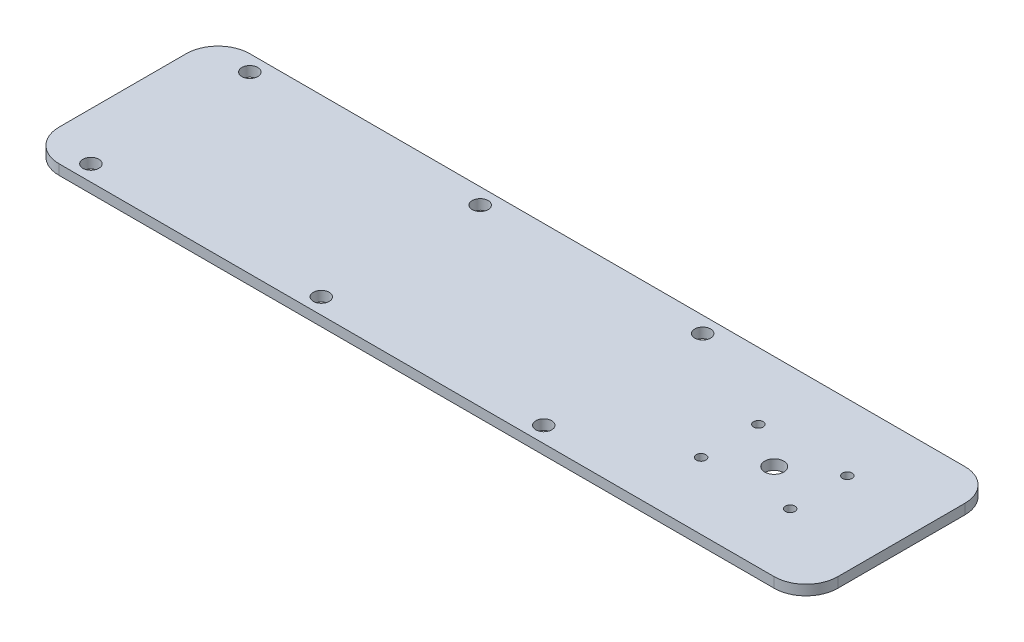
SolidWorks part; units mm, degrees
ref_plane "Front Plane" through (0, 0, 0) normal (0, 0, 1) x (1, 0, 0)
ref_plane "Top Plane" through (0, 0, 0) normal (0, 1, 0) x (1, 0, 0)
ref_plane "Right Plane" through (0, 0, 0) normal (1, 0, 0) x (0, 0, -1)
sketch "Sketch1" plane through (0, 0, 0) normal (0, 1, 0) x (1, 0, 0)
  line L0 (-55, 0) -> (0, 0) construction
  line L1 (-55, 30) -> (190, 30)
  line L2 (-55, 30) -> (-55, -30)
  line L3 (-55, -30) -> (190, -30)
  line L4 (190, 30) -> (190, -30)
  point P7 (150, 0)
  dimension "D1" = 60
  dimension "D2" = 55
  dimension "D3" = 150
  dimension "D4" = 40
extrude "Boss-Extrude1" add sketch "Sketch1" along normal blind 3.175
fillet "Fillet1" radius 10 4 edges at (-55, 1.5875, 30) (-55, 1.5875, -30) (190, 1.5875, 30) (190, 1.5875, -30)
hole_wizard "Ø6.0mm Dowel Hole1" positions "Sketch2" profile "Sketch3" hole size "Ø6.0" standard "DIN" end condition up to next
sketch "Sketch2" plane through (0, 3.175, 0) normal (0, 1, 0) x (1, 0, 0)
  point P0 (150, 0)
  dimension "D1" = 150
sketch "Sketch3" plane through (150, 3.175, 0) normal (1, 0, 0) x (0, 0, 1)
  line L0 (0, 0) -> (0, 3.175)
  line L1 (0, 3.175) -> (3, 3.175)
  line L2 (3, 3.175) -> (3, 0)
  line L5 (3, 0) -> (0, 0)
  line L11 (0, -6.35) -> (0, 107.95) construction
  dimension "Thru Hole Dia." = 6
  dimension "Thru Hole Depth" = 3.175
hole_wizard "Ø3.0mm Dowel Hole1" positions "Sketch4" profile "Sketch5" hole size "Ø3.0" standard "ANSI Metric" end condition up to next
sketch "Sketch4" plane through (0, 3.175, 0) normal (0, 1, 0) x (1, 0, 0)
  line L0 (164, -9) -> (136, -9) construction
  line L1 (164, -9) -> (164, 9) construction
  circle A0 centre (150, 0) radius 3 construction
  point P0 (164, -9)
  point P7 (136, -9)
  point P8 (136, 9)
  point P9 (164, 9)
  dimension "D3" = 28
  dimension "D4" = 18
  dimension "D5" = 14
  dimension "D6" = 9
  dimension "D1" = 2
  dimension "D2" = 2
sketch "Sketch5" plane through (164, 3.175, 9) normal (1, 0, 0) x (0, 0, 1)
  line L0 (0, 0) -> (0, 3.175)
  line L1 (0, 3.175) -> (1.5, 3.175)
  line L2 (1.5, 3.175) -> (1.5, 0)
  line L5 (1.5, 0) -> (0, 0)
  line L11 (0, -6.35) -> (0, 107.95) construction
  dimension "Thru Hole Dia." = 3
  dimension "Thru Hole Depth" = 3.175
hole_wizard "Ø5.0mm Dowel Hole1" positions "Sketch6" profile "Sketch7" hole size "Ø5.0" standard "DIN" end condition through all
sketch "Sketch6" plane through (0, 3.175, 0) normal (0, 1, 0) x (1, 0, 0)
  line L0 (-45, -30) -> (180, -30) construction
  line L1 (32.5, -25) -> (102.5, -25) construction
  line L2 (-55, 0) -> (190, 0) construction
  line L3 (-55, 20) -> (-55, -20) construction
  line L4 (190, -20) -> (190, 20) construction
  line L5 (67.5, 30) -> (67.5, -30) construction
  line L6 (180, 30) -> (-45, 30) construction
  line L8 (32.5, 25) -> (67.5, 25) construction
  line L10 (67.5, 25) -> (102.5, 25) construction
  point P0 (32.5, -25)
  point P10 (102.5, -25)
  point P24 (102.5, 25)
  point P25 (32.5, 25)
  point P26 (-40, -25)
  point P29 (-40, 25)
  dimension "D1" = 5
  dimension "D4" = 70
  dimension "D5" = 15
  dimension "D3" = 2
sketch "Sketch7" plane through (32.5, 3.175, 25) normal (1, 0, 0) x (0, 0, 1)
  line L0 (0, 0) -> (0, 3.175)
  line L1 (0, 3.175) -> (2.5, 3.175)
  line L2 (2.5, 3.175) -> (2.5, 0)
  line L5 (2.5, 0) -> (0, 0)
  line L11 (0, -6.35) -> (0, 107.95) construction
  dimension "Thru Hole Dia." = 5
  dimension "Thru Hole Depth" = 3.175
equation "\"Pivot to Pivot Dist\"= 150mm"
equation "\"D3@Sketch1\"=\"Pivot to Pivot Dist\""
equation "\"D1@Sketch2\"=\"Pivot to Pivot Dist\""
